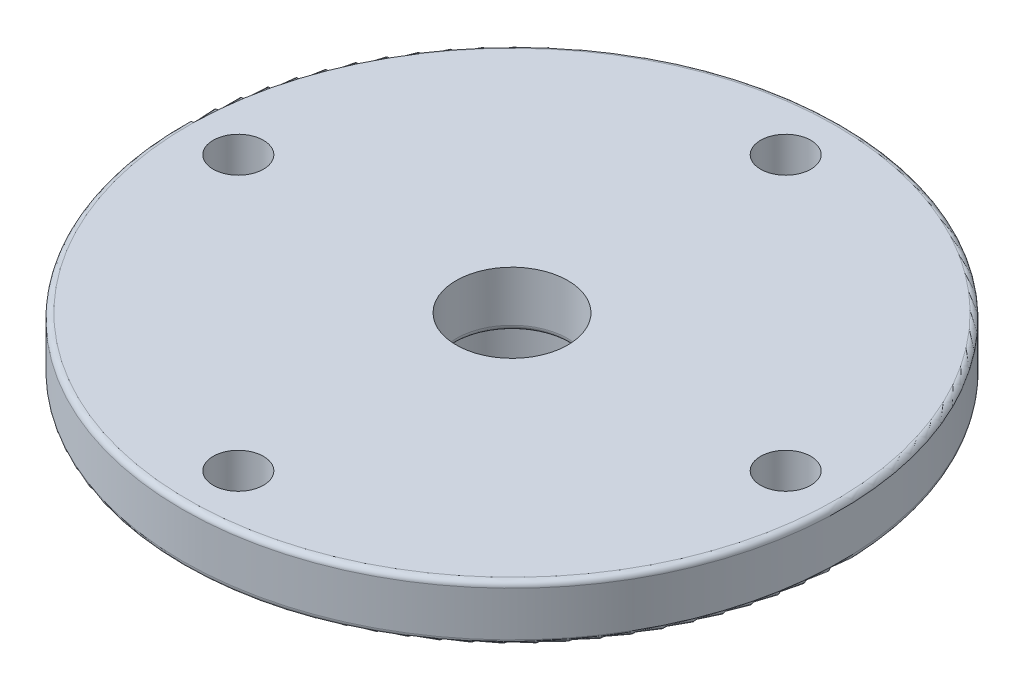
SolidWorks part; units mm, degrees
ref_plane "前视基准面" through (0, 0, 0) normal (0, 0, 1) x (1, 0, 0)
ref_plane "上视基准面" through (0, 0, 0) normal (0, 1, 0) x (1, 0, 0)
ref_plane "右视基准面" through (0, 0, 0) normal (1, 0, 0) x (0, 0, -1)
sketch "草图1" plane through (0, 0, 0) normal (0, 0, 1) x (1, 0, 0)
  line L0 (0, 105) -> (0, 115) construction
  line L3 (-6.5, 114) -> (-6.5, 105) construction
  line L4 (-6.5, 115) -> (-6.5, 105)
  line L5 (8.5, 105) -> (-8.5, 105) construction
  line L6 (5.5, 115) -> (-5.5, 115) construction
  line L7 (-6.5, 105) -> (-9.5, 105)
  line L8 (-9.5, 105) -> (-9.5, 115)
  line L9 (-9.5, 115) -> (-29.5, 115)
  line L10 (-29.5, 115) -> (-29.5, 120)
  line L11 (-29.5, 120) -> (-5, 120)
  line L12 (-6.5, 115) -> (-5, 115)
  line L13 (-5, 115) -> (-5, 120)
  dimension "D1" = 3
  dimension "D2" = 5
  dimension "D3" = 20
  dimension "D4" = 1.5
revolve "旋转1" add sketch "草图1" angle 360 about L0
sketch "草图2" plane through (0, 115, 0) normal (0, -1, 0) x (1, 0, 0)
  line L0 (0, 24.5) -> (0, -24.5)
  line L1 (24.5, 0) -> (-24.5, 0)
  circle A2 centre (0, 0) radius 24.5
  circle A3 centre (0, 0) radius 24.5
  dimension "D1" = 5
hole_wizard "M4 间隙孔1" positions "3D草图1" profile "草图3" hole size "M4" standard "GB"
sketch3d "3D草图1"
  line L0 (24.5, 115, 0) -> (-24.5, 115, 0) construction
  point P0 (-24.5, 115, 0)
  point P3 (0, 115, 24.5)
  point P6 (24.5, 115, 0)
  point P10 (0, 115, -24.5)
sketch "草图3" plane through (-24.5, 115, 0) normal (1, 0, 0) x (0, 0, -1)
  line L0 (0, 0) -> (0, 21.3519)
  line L1 (0, 21.3519) -> (2.25, 20)
  line L2 (2.25, 20) -> (2.25, 0)
  line L5 (2.25, 0) -> (0, 0)
  line L10 (0, 21.3519) -> (-2.25, 20) construction
  line L11 (0, -6.35) -> (0, 107.95) construction
  dimension "孔直径" = 4.5
  dimension "孔深度" = 20
  dimension "导头角度" = 118
fillet "圆角1" radius 0.5 5 edges at (0, 115, -5) (0, 120, -29.5) (0, 115, -29.5) (0, 105, -9.5) (0, 115, -9.5)
fillet "圆角2" radius 0.5 2 edges at (0, 105, -6.5) (0, 115, -6.5)
sketch "草图4" plane through (0, 0, 0) normal (1, 0, 0) x (0, 0, -1)
  line L0 (-9, 105) -> (9, 105) construction
  point P0 (0, 110)
  dimension "D1" = 5
hole_wizard "M3 螺纹孔1" positions "3D草图2" profile "草图5" tap size "M3" standard "GB"
sketch3d "3D草图2"
  point P0 (-6.5, 110, 0)
sketch "草图5" plane through (-6.5, 110, 0) normal (0, 1, 0) x (0, 0, -1)
  line L0 (0, 0) -> (0, 9.2511)
  line L1 (0, 9.2511) -> (1.25, 8.5)
  line L2 (1.25, 8.5) -> (1.25, 0)
  line L5 (1.25, 0) -> (0, 0)
  line L10 (0, 9.2511) -> (-1.25, 8.5) construction
  line L11 (0, -6.35) -> (0, 107.95) construction
  dimension "螺纹孔钻头直径" = 2.5
  dimension "螺纹孔钻头深度" = 8.5
  dimension "导头角度" = 118
cosmetic thread "孔螺蚊线1" parameters "D1"=3.1213, "D2"=3
